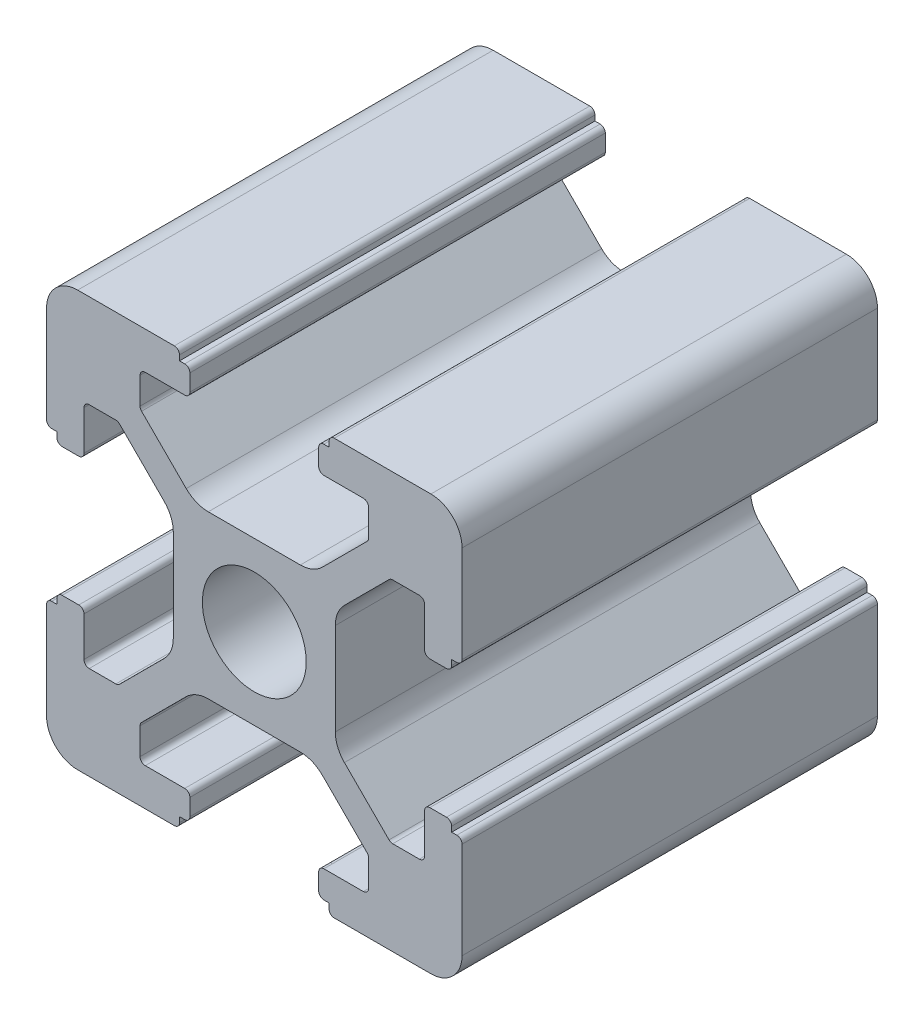
SolidWorks part; units mm, degrees
ref_plane "前视基准面" through (0, 0, 0) normal (0, 0, 1) x (1, 0, 0)
ref_plane "上视基准面" through (0, 0, 0) normal (0, 1, 0) x (1, 0, 0)
ref_plane "右视基准面" through (0, 0, 0) normal (1, 0, 0) x (0, 0, -1)
sketch "草图1" plane through (0, 0, 0) normal (0, 0, 1) x (1, 0, 0)
  line L0 (0, 0) -> (0, 5.5) construction
  line L1 (-8.5023, -10.0023) -> (-3.85, -10.0023)
  line L2 (-10.0023, -8.5023) -> (-10.0023, -3.85)
  line L3 (-8.5023, 10.0023) -> (-3.85, 10.0023)
  line L4 (10.0023, -8.5023) -> (10.0023, -3.85)
  line L5 (-10.0023, -10.0023) -> (10.0023, 10.0023) construction
  line L6 (-10.0023, 10.0023) -> (10.0023, -10.0023) construction
  line L7 (-2.218, -3.9) -> (2.218, -3.9)
  line L8 (-3.9, -2.218) -> (-3.9, 2.218)
  line L9 (-2.218, 3.9) -> (2.218, 3.9)
  line L10 (3.9, -2.218) -> (3.9, 2.218)
  line L11 (-3.9, -3.9) -> (3.9, 3.9) construction
  line L12 (-3.9, 3.9) -> (3.9, -3.9) construction
  line L13 (-5.25, -8.2) -> (-3.35, -8.2)
  line L14 (-8.2, -5.25) -> (-8.2, -3.35)
  line L15 (-5.25, 8.2) -> (-3.35, 8.2)
  line L16 (8.2, -5.25) -> (8.2, -3.35)
  line L17 (-8.2, -8.2) -> (8.2, 8.2) construction
  line L18 (-8.2, 8.2) -> (8.2, -8.2) construction
  line L19 (-7.95, 5.5) -> (-6.6642, 5.5)
  line L20 (0, 0) -> (5.5, 0) construction
  line L23 (-5.5, 7.95) -> (-5.5, 6.6642)
  line L26 (0, 0) -> (-0.5303, 0.5303)
  line L27 (3.2787, 4.3393) -> (5.4268, 6.4874)
  line L28 (0, 0) -> (0.5303, -0.5303)
  line L29 (5.5, 6.6642) -> (5.5, 7.95)
  line L30 (4.3393, 3.2787) -> (6.4874, 5.4268)
  line L31 (6.6642, 5.5) -> (7.95, 5.5)
  line L32 (4.3393, -3.2787) -> (6.4874, -5.4268)
  line L33 (3.2787, -4.3393) -> (5.4268, -6.4874)
  line L34 (-3.2787, -4.3393) -> (-5.4268, -6.4874)
  line L35 (-4.3393, -3.2787) -> (-6.4874, -5.4268)
  line L36 (-4.3393, 3.2787) -> (-6.4874, 5.4268)
  line L37 (-3.2787, 4.3393) -> (-5.4268, 6.4874)
  line L38 (3.1, -8.45) -> (3.1, -9.2523)
  line L39 (8.45, 3.1) -> (9.2523, 3.1)
  line L40 (-5.5, -6.6642) -> (-5.5, -7.95)
  line L41 (-6.6642, -5.5) -> (-7.95, -5.5)
  line L42 (5.5, -6.6642) -> (5.5, -7.95)
  line L43 (6.6642, -5.5) -> (7.95, -5.5)
  line L44 (9.2523, -3.1) -> (8.45, -3.1)
  line L46 (10.0023, 3.85) -> (10.0023, 8.5023)
  line L47 (8.2, 3.35) -> (8.2, 5.25)
  line L48 (-3.1, -9.2523) -> (-3.1, -8.45)
  line L49 (-8.45, -3.1) -> (-9.2523, -3.1)
  line L50 (-9.2523, 3.1) -> (-8.45, 3.1)
  line L51 (-3.1, 8.45) -> (-3.1, 9.2523)
  line L52 (3.1, 9.2523) -> (3.1, 8.45)
  line L53 (3.85, 10.0023) -> (8.5023, 10.0023)
  line L54 (3.35, 8.2) -> (5.25, 8.2)
  line L55 (-10.0023, 3.85) -> (-10.0023, 8.5023)
  line L56 (-8.2, 3.35) -> (-8.2, 5.25)
  line L57 (3.35, -8.2) -> (5.25, -8.2)
  line L58 (3.85, -10.0023) -> (8.5023, -10.0023)
  line L59 (9.7523, -3.6) -> (9.5023, -3.6)
  line L61 (9.7523, 3.6) -> (9.5023, 3.6)
  line L62 (9.5023, -3.6) -> (9.5023, -3.35)
  line L63 (3.6, -9.7523) -> (3.6, -9.5023)
  line L64 (3.35, -9.5023) -> (3.6, -9.5023)
  line L65 (9.5023, 3.35) -> (9.5023, 3.6)
  line L66 (-3.6, -9.5023) -> (-3.35, -9.5023)
  line L67 (-3.6, -9.7523) -> (-3.6, -9.5023)
  line L68 (-9.7523, -3.6) -> (-9.5023, -3.6)
  line L69 (-9.5023, -3.35) -> (-9.5023, -3.6)
  line L70 (-9.5023, 3.6) -> (-9.5023, 3.35)
  line L71 (-9.7523, 3.6) -> (-9.5023, 3.6)
  line L72 (-3.6, 9.7523) -> (-3.6, 9.5023)
  line L73 (-3.35, 9.5023) -> (-3.6, 9.5023)
  line L74 (3.6, 9.5023) -> (3.35, 9.5023)
  line L75 (3.6, 9.7523) -> (3.6, 9.5023)
  circle A0 centre (0, 0) radius 2.5
  arc A1 (10.0023, 8.5023) -> (8.5023, 10.0023) centre (8.5023, 8.5023) ccw
  arc A2 (8.5023, -10.0023) -> (10.0023, -8.5023) centre (8.5023, -8.5023) ccw
  arc A3 (-10.0023, -8.5023) -> (-8.5023, -10.0023) centre (-8.5023, -8.5023) ccw
  arc A4 (-10.0023, 8.5023) -> (-8.5023, 10.0023) centre (-8.5023, 8.5023) cw
  arc A5 (-9.5023, -3.35) -> (-9.2523, -3.1) centre (-9.2523, -3.35) cw
  arc A6 (-9.7523, -3.6) -> (-10.0023, -3.85) centre (-9.7523, -3.85) ccw
  arc A7 (-8.45, -3.1) -> (-8.2, -3.35) centre (-8.45, -3.35) cw
  arc A8 (-7.95, -5.5) -> (-8.2, -5.25) centre (-7.95, -5.25) cw
  arc A9 (-6.4874, -5.4268) -> (-6.6642, -5.5) centre (-6.6642, -5.25) cw
  arc A10 (-5.4268, -6.4874) -> (-5.5, -6.6642) centre (-5.25, -6.6642) ccw
  arc A11 (-5.5, -7.95) -> (-5.25, -8.2) centre (-5.25, -7.95) ccw
  arc A12 (-3.6, -9.7523) -> (-3.85, -10.0023) centre (-3.85, -9.7523) cw
  arc A13 (-3.35, -9.5023) -> (-3.1, -9.2523) centre (-3.35, -9.2523) ccw
  arc A14 (-3.1, -8.45) -> (-3.35, -8.2) centre (-3.35, -8.45) ccw
  arc A15 (3.1, -8.45) -> (3.35, -8.2) centre (3.35, -8.45) cw
  arc A16 (5.5, -7.95) -> (5.25, -8.2) centre (5.25, -7.95) cw
  arc A17 (5.4268, -6.4874) -> (5.5, -6.6642) centre (5.25, -6.6642) cw
  arc A18 (6.4874, -5.4268) -> (6.6642, -5.5) centre (6.6642, -5.25) ccw
  arc A19 (7.95, -5.5) -> (8.2, -5.25) centre (7.95, -5.25) ccw
  arc A20 (8.45, -3.1) -> (8.2, -3.35) centre (8.45, -3.35) ccw
  arc A21 (9.5023, -3.35) -> (9.2523, -3.1) centre (9.2523, -3.35) ccw
  arc A22 (9.7523, -3.6) -> (10.0023, -3.85) centre (9.7523, -3.85) cw
  arc A23 (3.35, -9.5023) -> (3.1, -9.2523) centre (3.35, -9.2523) cw
  arc A24 (3.6, -9.7523) -> (3.85, -10.0023) centre (3.85, -9.7523) ccw
  arc A25 (7.95, 5.5) -> (8.2, 5.25) centre (7.95, 5.25) cw
  arc A26 (8.2, 3.35) -> (8.45, 3.1) centre (8.45, 3.35) ccw
  arc A27 (9.5023, 3.35) -> (9.2523, 3.1) centre (9.2523, 3.35) cw
  arc A28 (9.7523, 3.6) -> (10.0023, 3.85) centre (9.7523, 3.85) ccw
  arc A29 (6.6642, 5.5) -> (6.4874, 5.4268) centre (6.6642, 5.25) ccw
  arc A30 (5.4268, 6.4874) -> (5.5, 6.6642) centre (5.25, 6.6642) ccw
  arc A31 (5.5, 7.95) -> (5.25, 8.2) centre (5.25, 7.95) ccw
  arc A32 (3.1, 8.45) -> (3.35, 8.2) centre (3.35, 8.45) ccw
  arc A33 (3.6, 9.7523) -> (3.85, 10.0023) centre (3.85, 9.7523) cw
  arc A34 (3.35, 9.5023) -> (3.1, 9.2523) centre (3.35, 9.2523) ccw
  arc A35 (-9.7523, 3.6) -> (-10.0023, 3.85) centre (-9.7523, 3.85) cw
  arc A36 (-9.5023, 3.35) -> (-9.2523, 3.1) centre (-9.2523, 3.35) ccw
  arc A37 (-8.45, 3.1) -> (-8.2, 3.35) centre (-8.45, 3.35) ccw
  arc A38 (-8.2, 5.25) -> (-7.95, 5.5) centre (-7.95, 5.25) cw
  arc A39 (-6.4874, 5.4268) -> (-6.6642, 5.5) centre (-6.6642, 5.25) ccw
  arc A40 (-5.4268, 6.4874) -> (-5.5, 6.6642) centre (-5.25, 6.6642) cw
  arc A41 (-5.5, 7.95) -> (-5.25, 8.2) centre (-5.25, 7.95) cw
  arc A42 (-3.1, 8.45) -> (-3.35, 8.2) centre (-3.35, 8.45) cw
  arc A43 (-3.1, 9.2523) -> (-3.35, 9.5023) centre (-3.35, 9.2523) ccw
  arc A44 (-3.6, 9.7523) -> (-3.85, 10.0023) centre (-3.85, 9.7523) ccw
  arc A45 (-4.3393, 3.2787) -> (-3.9, 2.218) centre (-5.4, 2.218) cw
  arc A46 (-3.2787, 4.3393) -> (-2.218, 3.9) centre (-2.218, 5.4) ccw
  arc A47 (3.2787, 4.3393) -> (2.218, 3.9) centre (2.218, 5.4) cw
  arc A48 (4.3393, 3.2787) -> (3.9, 2.218) centre (5.4, 2.218) ccw
  arc A49 (4.3393, -3.2787) -> (3.9, -2.218) centre (5.4, -2.218) cw
  arc A50 (3.2787, -4.3393) -> (2.218, -3.9) centre (2.218, -5.4) ccw
  arc A51 (-4.3393, -3.2787) -> (-3.9, -2.218) centre (-5.4, -2.218) ccw
  arc A52 (-2.218, -3.9) -> (-3.2787, -4.3393) centre (-2.218, -5.4) ccw
  point P0 (0, 0)
  point P7 (10.0023, 0)
  point P62 (0, 0)
  point P76 (0, 0)
  point P92 (-8.2, -5.5)
  point P99 (0, 0)
  point P106 (-5.5, -8.2)
  point P117 (5.5, -8.2)
  point P124 (8.2, -5.5)
  point P137 (8.2, 5.5)
  point P140 (8.2, 3.1)
  point P147 (6.5607, 5.5)
  point P152 (5.5, 8.2)
  point P167 (-8.2, 5.5)
  point P174 (-5.5, 8.2)
  dimension "D1" = 1.5
  dimension "D5" = 0.25
  dimension "D6" = 1.5
  dimension "D2" = 4
  dimension "D3" = 4
  dimension "D4" = 4
extrude "凸台-拉伸1" add sketch "草图1" along normal blind 20 contours A52 L7 A50 L33 A17 L42 A16 L57 A15 L38 A23 L64 L63 A24 L58 A2 L4 A22 L59 L62 A21 L44 A20 L16 A19 L43 A18 L32 A49 L10 A48 L30 A29 L31 A25 L47 A26 L39 A27 L65 L61 A28 L46 A1 L53 A33 L75 L74 A34 L52 A32
